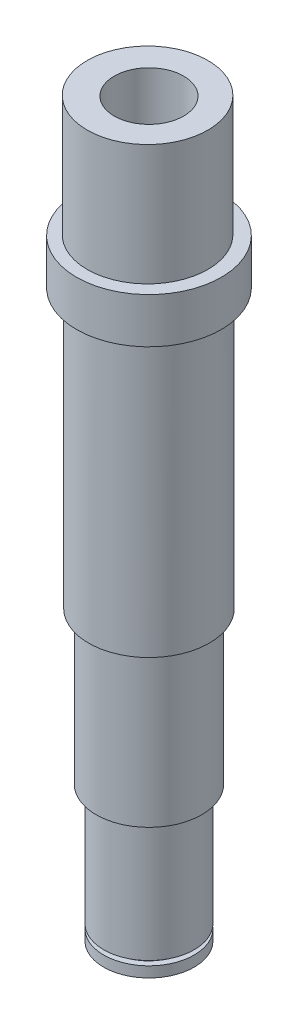
SolidWorks part; units mm, degrees
ref_plane "Front Plane" through (0, 0, 0) normal (0, 0, 1) x (1, 0, 0)
ref_plane "Top Plane" through (0, 0, 0) normal (0, 1, 0) x (1, 0, 0)
ref_plane "Right Plane" through (0, 0, 0) normal (1, 0, 0) x (0, 0, -1)
sketch "Sketch1" plane through (0, 0, 0) normal (0, 1, 0) x (1, 0, 0)
  circle A0 centre (0, 0) radius 20
  dimension "D1" = 40
extrude "Boss-Extrude1" add sketch "Sketch1" along normal blind 142.5
sketch "Sketch2" plane through (0, 142.5, 0) normal (0, 1, 0) x (1, 0, 0)
  circle A0 centre (0, 0) radius 24
  dimension "D1" = 48
extrude "Boss-Extrude2" add sketch "Sketch2" along normal blind 15
sketch "Sketch3" plane through (0, 157.5, 0) normal (0, 1, 0) x (1, 0, 0)
  circle A0 centre (-0.4638, 0) radius 20
  dimension "D1" = 40
extrude "Boss-Extrude3" add sketch "Sketch3" along normal blind 40
sketch "Sketch5" plane through (0, 0, 0) normal (0, -1, 0) x (1, 0, 0)
  circle A0 centre (0, 0) radius 15
  dimension "D1" = 30
extrude "Boss-Extrude4" add sketch "Sketch5" along normal blind 45
sketch "Sketch4" plane through (0, 197.5, 0) normal (0, 1, 0) x (1, 0, 0)
  circle A0 centre (0, 0) radius 11.5
  dimension "D1" = 23
extrude "Cut-Extrude1" cut sketch "Sketch4" against normal through all both and the other way through all
sketch "Sketch7" plane through (0, 0, 0) normal (1, 0, 0) x (0, 0, -1)
  line L0 (0, -40.1309) -> (0, 39.5233) construction
  line L1 (15, -45) -> (15, 0) construction
  line L2 (15, -40) -> (13, -40)
  line L3 (15, -40) -> (15, -41.5)
  line L4 (15, -41.5) -> (13, -41.5)
  line L5 (13, -40) -> (13, -41.5)
  line L6 (-15, -45) -> (15, -45) construction
  dimension "D1" = 2
  dimension "D2" = 1.5
  dimension "D3" = 5
revolve "Cut-Revolve1" cut sketch "Sketch7" angle 360 about L0
sketch "Sketch10" plane through (0, 0, 0) normal (0, 0, 1) x (1, 0, 0)
  line L0 (0, -22.1684) -> (0, 47) construction
  line L1 (-20, 0) -> (-17.5, 0)
  line L2 (-20, 0) -> (-20, 50.5)
  line L3 (-20, 50.5) -> (-17.5, 50.5)
  line L4 (-17.5, 0) -> (-17.5, 50.5)
  dimension "D1" = 2.5
  dimension "D2" = 50.5
revolve "Cut-Revolve2" cut sketch "Sketch10" angle 360 about L0
